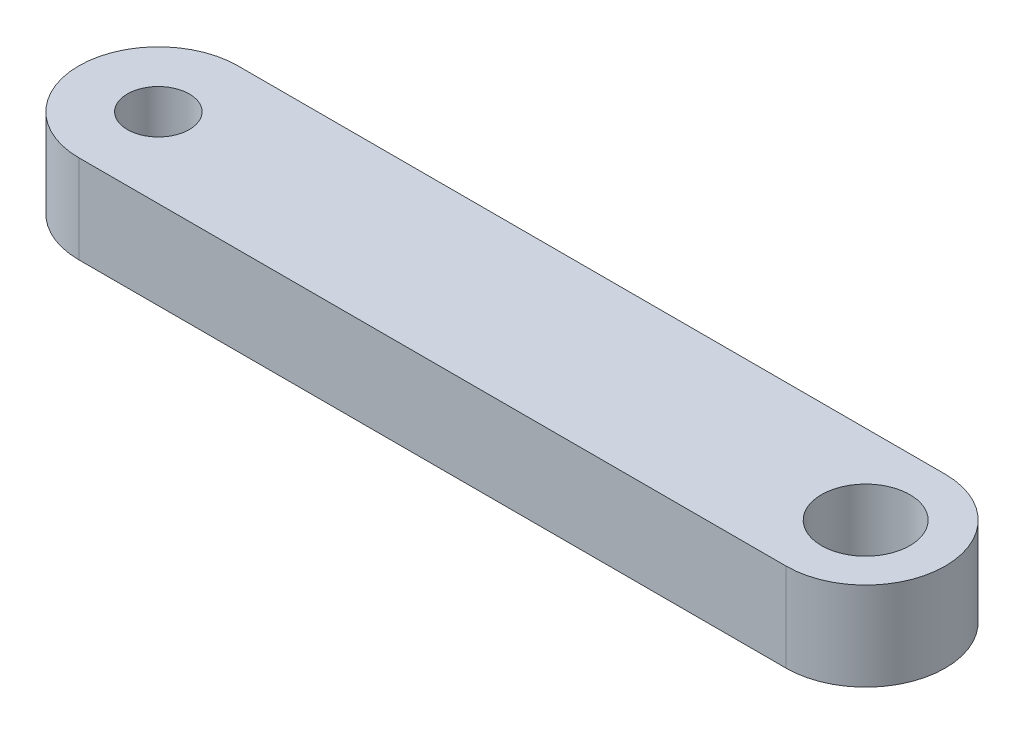
SolidWorks part; units mm, degrees
ref_plane "Front Plane" through (0, 0, 0) normal (0, 0, 1) x (1, 0, 0)
ref_plane "Top Plane" through (0, 0, 0) normal (0, 1, 0) x (1, 0, 0)
ref_plane "Right Plane" through (0, 0, 0) normal (1, 0, 0) x (0, 0, -1)
sketch "Sketch1" plane through (0, 0, 0) normal (0, 1, 0) x (1, 0, 0)
  line L0 (0, 0) -> (40, 0) construction
  line L1 (0, 4.5) -> (40, 4.5)
  line L2 (0, -4.5) -> (40, -4.5)
  arc A0 (0, 4.5) -> (0, -4.5) centre (0, 0) ccw
  arc A1 (40, -4.5) -> (40, 4.5) centre (40, 0) ccw
  point P3 (20, 0)
  dimension "D1" = 4.5
  dimension "D2" = 40
extrude "Boss-Extrude1" add sketch "Sketch1" along normal blind 5
sketch "Sketch2" plane through (0, 5, 0) normal (0, 1, 0) x (1, 0, 0)
  circle A0 centre (0, 0) radius 1.75
extrude "Cut-Extrude1" cut sketch "Sketch2" against normal up to surface (5 mm away) contours A0 up to face at (20, 0, 0)
sketch "Sketch4" plane through (0, 0, 0) normal (0, -1, 0) x (1, 0, 0)
  circle A0 centre (40, 0) radius 0.05
sketch "Sketch5" plane through (0, 5, 0) normal (0, 1, 0) x (1, 0, 0)
  circle A0 centre (40, 0) radius 2.5
  arc A2 (40, -4.5) -> (40, 4.5) centre (40, 0) ccw construction
  point P6 (44.5, 0)
  dimension "D1" = 5
  dimension "D2" = 4.5
  dimension "D3" = 4.5
extrude "Cut-Extrude2" cut sketch "Sketch5" against normal blind 10
